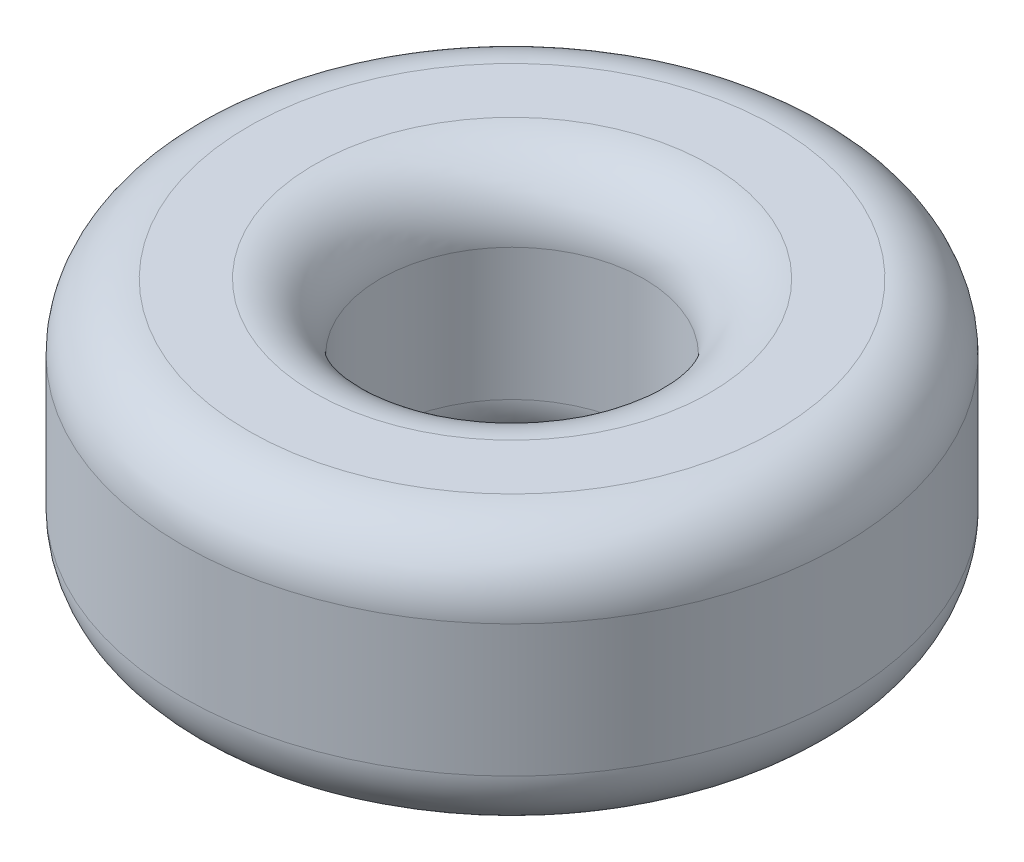
SolidWorks part; units mm, degrees
ref_plane "Front Plane" through (0, 0, 0) normal (0, 0, 1) x (1, 0, 0)
ref_plane "Top Plane" through (0, 0, 0) normal (0, 1, 0) x (1, 0, 0)
ref_plane "Right Plane" through (0, 0, 0) normal (1, 0, 0) x (0, 0, -1)
sketch "Sketch1" plane through (0, 0, 0) normal (0, 1, 0) x (1, 0, 0)
  circle A0 centre (0, 0) radius 50
  circle A1 centre (0, 0) radius 20
  dimension "D1" = 100
  dimension "D2" = 40
extrude "Boss-Extrude1" add sketch "Sketch1" along normal blind 40
fillet "Fillet1" radius 10 4 edges at (0, 0, 20) (0, 0, 50) (0, 40, 20) (0, 40, 50)
